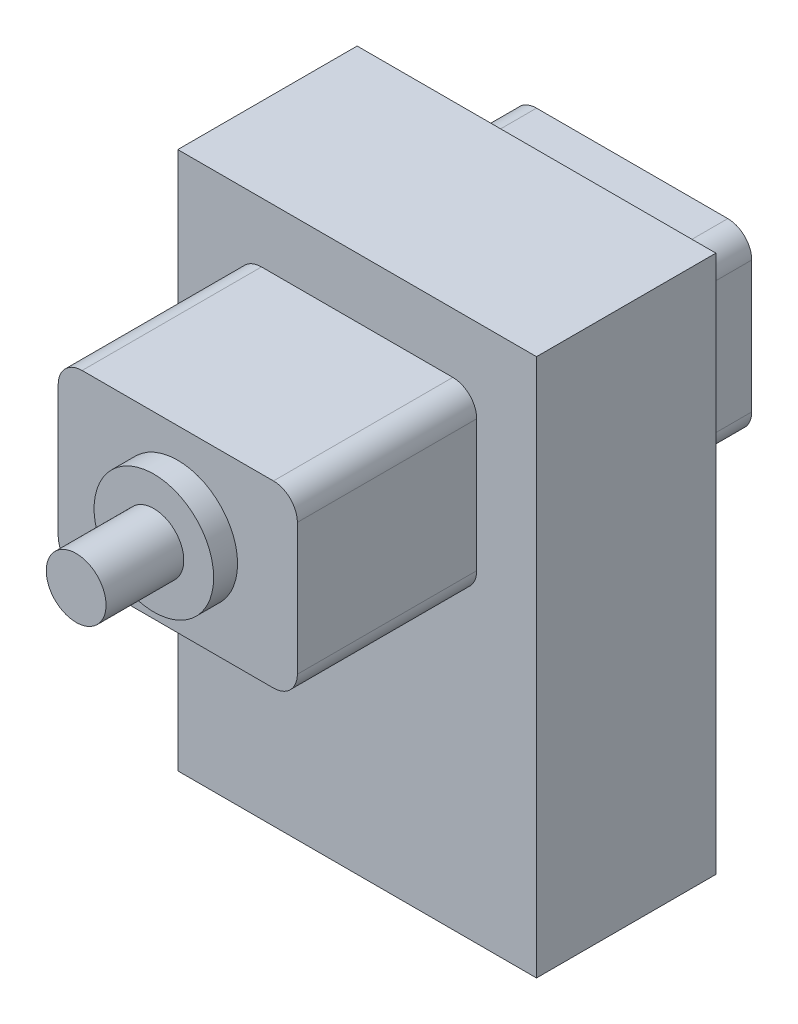
SolidWorks part; units mm, degrees
material "PVC 0.007 Plasticized"
ref_plane "Ön Düzlem" through (0, 0, 0) normal (0, 0, 1) x (1, 0, 0)
ref_plane "Üst Düzlem" through (0, 0, 0) normal (0, 1, 0) x (1, 0, 0)
ref_plane "Sağ Düzlem" through (0, 0, 0) normal (1, 0, 0) x (0, 0, -1)
sketch "Sketch3" plane through (0, 0, 0) normal (0, 0, 1) x (1, 0, 0)
  line L1 (-30, 45) -> (0, 45)
  line L2 (-30, 45) -> (-30, 0)
  line L3 (-30, 0) -> (0, 0)
  line L4 (0, 45) -> (0, 0)
  dimension "D1" = 30
  dimension "D2" = 45
extrude "Boss-Extrude1" add sketch "Sketch3" along normal blind 15
sketch "Sketch4" plane through (0, 0, 15) normal (0, 0, 1) x (1, 0, 0)
  line L0 (0, 0) -> (0, 45) construction
  line L1 (-25, 40) -> (-5, 40)
  line L2 (-25, 40) -> (-25, 25)
  line L3 (-25, 25) -> (-5, 25)
  line L4 (-5, 40) -> (-5, 25)
  line L5 (0, 45) -> (-30, 45) construction
  line L6 (-30, 45) -> (-30, 0) construction
  dimension "D1" = 15
  dimension "D2" = 5
  dimension "D3" = 5
  dimension "D4" = 5
extrude "Boss-Extrude2" add sketch "Sketch4" along normal blind 15
sketch "Sketch5" plane through (0, 0, 0) normal (0, 0, -1) x (-1, 0, 0)
  line L0 (30, 45) -> (30, 0) construction
  line L1 (5, 40) -> (25, 40)
  line L2 (5, 40) -> (5, 25)
  line L3 (5, 25) -> (25, 25)
  line L4 (25, 40) -> (25, 25)
  line L5 (0, 0) -> (0, 45) construction
  line L6 (0, 45) -> (30, 45) construction
  dimension "D1" = 15
  dimension "D2" = 5
  dimension "D3" = 5
  dimension "D4" = 5
extrude "Boss-Extrude3" add sketch "Sketch5" along normal blind 8
fillet "Fillet1" radius 2 8 edges at (-25, 40, 22.5) (-25, 25, 22.5) (-5, 25, 22.5) (-5, 40, 22.5) (-5, 25, -4) (-25, 25, -4) (-5, 40, -4) (-25, 40, -4)
sketch "Sketch6" plane through (0, 0, 30) normal (0, 0, 1) x (1, 0, 0)
  line L0 (-5, 27) -> (-5, 38) construction
  line L1 (-23, 25) -> (-7, 25) construction
  circle A0 centre (-15, 32.5) radius 5
  point P4 (-5, 32.5)
  dimension "D1" = 10
  dimension "D2" = 10
  dimension "D3" = 7.5
extrude "Boss-Extrude4" add sketch "Sketch6" along normal blind 2
sketch "Sketch7" plane through (0, 0, 32) normal (0, 0, 1) x (1, 0, 0)
  circle A0 centre (-15, 32.5) radius 2.5
  circle A1 centre (-15, 32.5) radius 5 construction
  dimension "D1" = 5
extrude "Boss-Extrude5" add sketch "Sketch7" along normal blind 6.5 contours A0
equation "\"7.5.00mm\"=5"
